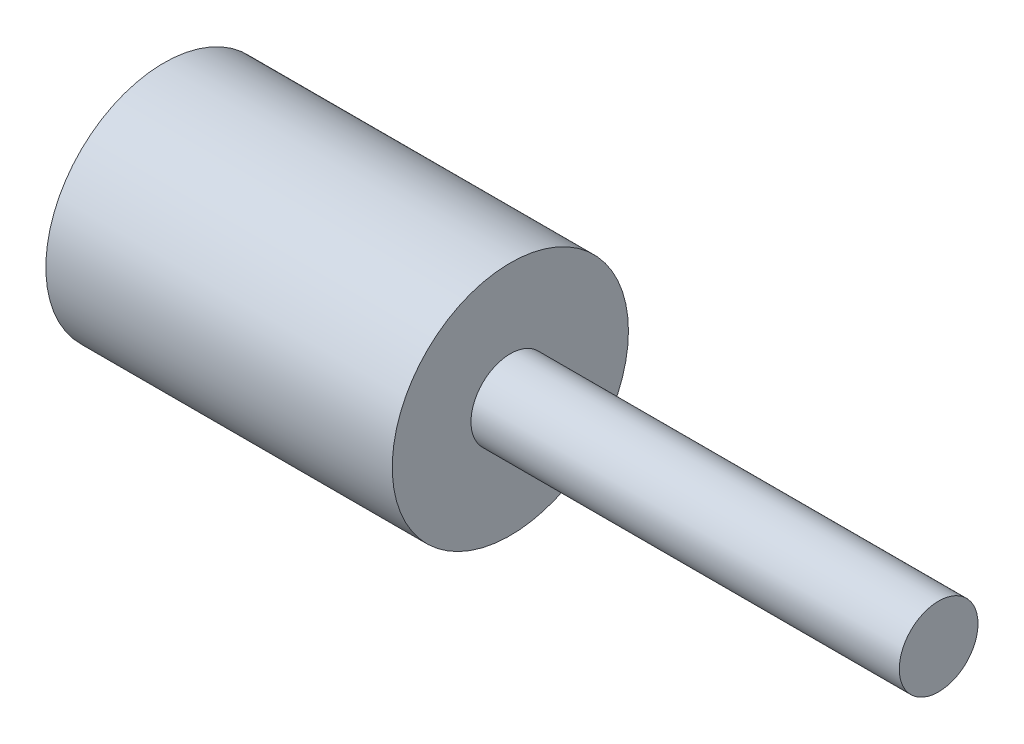
SolidWorks part; units mm, degrees
ref_plane "Front Plane" through (0, 0, 0) normal (0, 0, 1) x (1, 0, 0)
ref_plane "Top Plane" through (0, 0, 0) normal (0, 1, 0) x (1, 0, 0)
ref_plane "Right Plane" through (0, 0, 0) normal (1, 0, 0) x (0, 0, -1)
sketch "Sketch1" plane through (0, 0, 0) normal (0, 1, 0) x (1, 0, 0)
  line L8 (0, 0) -> (0, 7.5)
  line L9 (0, 7.5) -> (22, 7.5)
  line L10 (22, 7.5) -> (22, 2.5)
  line L11 (22, 2.5) -> (49.2, 2.5)
  line L16 (49.2, 2.5) -> (49.2, 0)
  line L17 (49.2, 0) -> (0, 0)
  dimension "D1" = 7.5
  dimension "D4" = 22
  dimension "D5" = 27.2
revolve "Revolve1" add sketch "Sketch1" angle 360 about L17
sketch "Sketch2" plane through (0, 0, 0) normal (-1, 0, 0) x (0, 0, 1)
  circle A0 centre (0, 0) radius 3.75
  dimension "D1" = 7.5
extrude "Cut-Extrude1" cut sketch "Sketch2" against normal blind 15
sketch "Sketch3" plane through (0, 0, 0) normal (0, 0, 1) x (1, 0, 0)
  circle A0 centre (4.906, 0) radius 1.5
  dimension "D1" = 3
extrude "Cut-Extrude2" cut sketch "Sketch3" against normal blind 10
ref_plane "Plane1" through (0, 0, -7.5) normal (0, 0, 1) x (1, 0, 0)
fillet "Fillet1" radius 0.5 1 edges at (6.3732, 0.3117, -7.4935)
